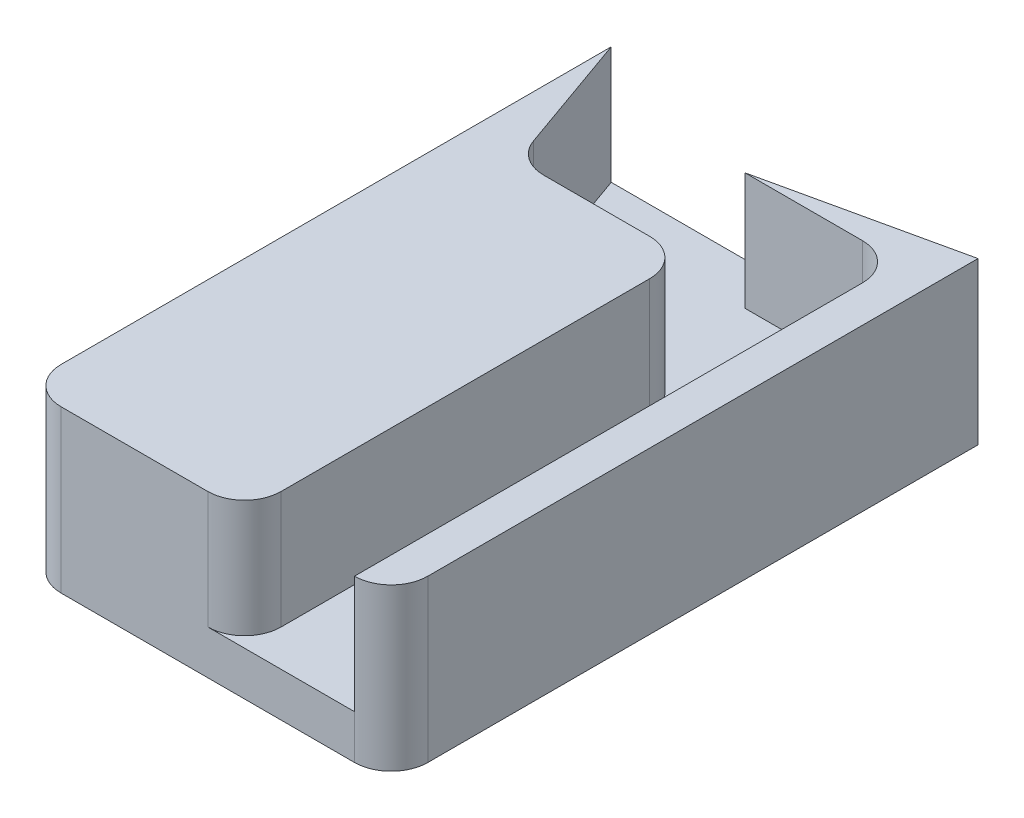
SolidWorks part; units mm, degrees
ref_plane "Front Plane" through (0, 0, 0) normal (0, 0, 1) x (1, 0, 0)
ref_plane "Top Plane" through (0, 0, 0) normal (0, 1, 0) x (1, 0, 0)
ref_plane "Right Plane" through (0, 0, 0) normal (1, 0, 0) x (0, 0, -1)
sketch "Sketch1" plane through (0, 0, 0) normal (0, 1, 0) x (1, 0, 0)
  line L1 (-80.9455, -38.5333) -> (-30.9455, -38.5333)
  line L2 (-80.9455, -38.5333) -> (-80.9455, -118.5333)
  line L3 (-80.9455, -118.5333) -> (-30.9455, -118.5333)
  line L4 (-30.9455, -38.5333) -> (-30.9455, -118.5333)
  dimension "D1" = 80
  dimension "D2" = 50
extrude "Boss-Extrude1" add sketch "Sketch1" along normal blind 6
sketch "Sketch2" plane through (0, 6, 0) normal (0, 1, 0) x (1, 0, 0)
  line L0 (-80.9455, -118.5333) -> (-50.9455, -118.5333)
  line L1 (-80.9455, -118.5333) -> (-30.9455, -118.5333) construction
  line L2 (-50.9455, -118.5333) -> (-50.9455, -58.2928)
  line L3 (-50.9455, -58.2928) -> (-73.9455, -58.2928)
  line L4 (-73.9455, -58.2928) -> (-80.9455, -38.5333)
  line L5 (-80.9455, -38.5333) -> (-80.9455, -118.5333) construction
  line L6 (-30.9455, -38.5333) -> (-30.9455, -118.5333)
  line L7 (-30.9455, -118.5333) -> (-35.9455, -118.5333)
  line L8 (-35.9455, -118.5333) -> (-35.9455, -44.2928)
  line L9 (-30.9455, -38.5333) -> (-56.9455, -44.2928)
  line L10 (-56.9455, -44.2928) -> (-35.9455, -44.2928)
  point P14 (0, 0)
  point P18 (0, 0)
  line M5 (-80.9455, -38.5333) -> (-80.9455, -118.5333)
  line M6 (-80.9455, -118.5333) -> (-30.9455, -118.5333)
  line M7 (-30.9455, -118.5333) -> (-30.9455, -38.5333)
  dimension "D1" = 23
  dimension "D2" = 30
  dimension "D3" = 5
  dimension "D4" = 14
  dimension "D5" = 21
  dimension "D6" = 26
extrude "Boss-Extrude2" add sketch "Sketch2" along normal blind 16 contours L3 L4 L2 M5 M6 | L9 L10 L8 M6 M7
fillet "Fillet1" radius 5 2 edges at (-50.9455, 14, 58.2928) (-73.9455, 14, 58.2928)
fillet "Fillet2" radius 5 1 edges at (-35.9455, 14, 44.2928)
sketch "Sketch3" plane through (0, 0, 58.2928) normal (0, 0, -1) x (-1, 0, 0)
  line L2 (55.9455, 16.8679) -> (70.4123, 16.8679) construction
  line L3 (70.4123, 6) -> (55.9455, 6) construction
  line L4 (63.1789, 6) -> (63.1789, 22) construction
  line L5 (55.9455, 22) -> (70.4123, 22) construction
  line L6 (55.9455, 22) -> (55.9455, 6) construction
  line L7 (70.4123, 6) -> (70.4123, 22) construction
  line L8 (56.9455, 22) -> (56.9455, 6) construction
  line L9 (56.9455, 12) -> (70.4123, 12) construction
  circle A0 centre (59.1289, 16.8679) radius 2.6
  circle A1 centre (67.2289, 16.8679) radius 2.6
  point P19 (63.1789, 16.8679)
  dimension "D1" = 5.2
  dimension "D2" = 5.2
  dimension "D3" = 4.05
  dimension "D4" = 4.05
  dimension "D5" = 6
  dimension "D6" = 8.1
  dimension "D7" = 5.1321
extrude "Cut-Extrude1" cut sketch "Sketch3" against normal blind 10
sketch "Sketch4" plane through (0, 0, 0) normal (0, -1, 0) x (1, 0, 0)
  line L0 (-80.9455, 38.5333) -> (-80.9455, 118.5333) construction
  line L1 (-77.9455, 116.0333) -> (-53.9455, 116.0333)
  line L2 (-77.9455, 116.0333) -> (-77.9455, 68.2833)
  line L3 (-77.9455, 68.2833) -> (-53.9455, 68.2833)
  line L4 (-53.9455, 116.0333) -> (-53.9455, 68.2833)
  line L5 (-80.9455, 118.5333) -> (-30.9455, 118.5333) construction
  dimension "D1" = 24
  dimension "D2" = 47.75
  dimension "D3" = 3
  dimension "D4" = 2.5
extrude "Cut-Extrude3" cut sketch "Sketch4" against normal blind 20
sketch "Sketch5" plane through (0, 0, 68.2833) normal (0, 0, 1) x (1, 0, 0)
  line L0 (-77.9455, 20) -> (-53.9455, 20) construction
  line L1 (-77.9108, 10) -> (-53.9455, 10)
  line L2 (-77.9108, 10) -> (-77.9108, 0)
  line L3 (-77.9108, 0) -> (-53.9455, 0)
  line L4 (-53.9455, 10) -> (-53.9455, 0)
  dimension "D1" = 10
extrude "Boss-Extrude3" add sketch "Sketch5" along normal blind 16
fillet "Fillet3" radius 5 3 edges at (-30.9455, 11, 118.5333) (-80.9455, 11, 118.5333) (-50.9455, 14, 118.5333)
sketch "Sketch11" plane through (0, 22, 0) normal (0, 1, 0) x (1, 0, 0)
  line L0 (-78.3017, -45.9961) -> (-62.4939, -58.2928)
  line L1 (-75.1253, -54.9625) -> (-80.9455, -38.5333) construction
  line L2 (-55.9455, -58.2928) -> (-70.4123, -58.2928) construction
  line L3 (-78.3017, -45.9961) -> (-75.1253, -54.9625)
  line L5 (-62.4939, -58.2928) -> (-70.4123, -58.2928)
  line L7 (-75.1253, -54.9625) -> (-80.9455, -38.5333) construction
  line L8 (-61.5353, -51.207) -> (-61.5353, -58.2928) construction
  line L9 (-78.3017, -45.9961) -> (-73.9455, -58.2928) construction
  line L10 (-62.4939, -58.2928) -> (-73.9455, -58.2928) construction
  arc A0 (-75.1253, -54.9625) -> (-70.4123, -58.2928) centre (-70.4123, -53.2928) ccw
  point P17 (-62.4939, -58.2928)
  dimension "D3" = 5
  dimension "D1" = 9.5124
  dimension "D2" = 20.0274
  dimension "D4" = 109.507
  dimension "D6" = 13.0455
  dimension "D7" = 11.4516
